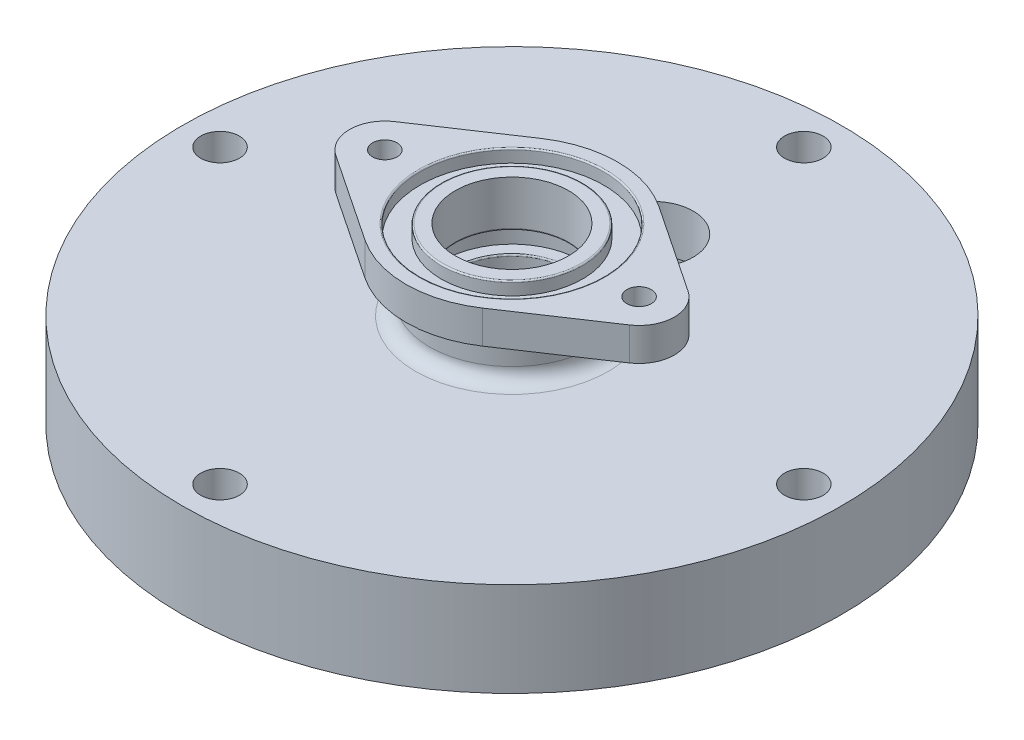
SolidWorks part; units mm, degrees
material "ABS"
ref_plane "Ön Düzlem" through (0, 0, 0) normal (0, 0, 1) x (1, 0, 0)
ref_plane "Üst Düzlem" through (0, 0, 0) normal (0, 1, 0) x (1, 0, 0)
ref_plane "Sağ Düzlem" through (0, 0, 0) normal (1, 0, 0) x (0, 0, -1)
sketch "Çizim1" plane through (0, 0, 0) normal (0, 1, 0) x (1, 0, 0)
  circle A0 centre (0, 0) radius 70
  dimension "D1" = 140
extrude "Yükseklik-Ekstrüzyon1" add sketch "Çizim1" along normal blind 20
sketch "Çizim2" plane through (0, 0, 0) normal (0, -1, 0) x (1, 0, 0)
  circle A0 centre (0, 0) radius 50.03
  circle A1 centre (0, 0) radius 45
  circle A2 centre (0, 0) radius 41
  circle A3 centre (0, 0) radius 17.35
  dimension "D1" = 100.06
  dimension "D2" = 90
  dimension "D3" = 82
  dimension "D4" = 34.7
extrude "Kes-Ekstrüzyon1" cut sketch "Çizim2" against normal blind 10 contours A0 A1 | A2 A3
sketch "Çizim4" plane through (0, 0, 0) normal (0, 0, 1) x (1, 0, 0)
  line L0 (-41, 0) -> (-13.6, 0)
  line L1 (-41, 0) -> (41, 0) construction
  line L2 (-45, 0) -> (45, 0) construction
  line L3 (-17.35, 0) -> (17.35, 0) construction
  line L4 (-17.35, 10) -> (-13.6, 0)
  line L8 (-17.35, 10) -> (17.35, 10) construction
  line L9 (-41, 10) -> (41, 10) construction
  line L10 (-17.35, 0) -> (-17.35, 10)
  line L11 (0, 0) -> (0, 30.5491)
  dimension "D1" = 27.4
revolve "Kes-Döndür1" cut sketch "Çizim4" angle 360 about L11
sketch "Çizim5" plane through (0, 20, 0) normal (0, 1, 0) x (1, 0, 0)
  circle A0 centre (0, 0) radius 17.5
  dimension "D1" = 35
extrude "Yükseklik-Ekstrüzyon2" add sketch "Çizim5" along normal blind 10
sketch "Çizim7" plane through (0, 30, 0) normal (0, 1, 0) x (1, 0, 0)
  line L2 (31.1667, -6.2361) -> (12.5, -18.7083)
  line L3 (31.1667, 6.2361) -> (12.5, 18.7083)
  line L4 (-12.5, -18.7083) -> (-31.1667, -6.2361)
  line L5 (-12.5, 18.7083) -> (-31.1667, 6.2361)
  arc A0 (12.5, 18.7083) -> (-12.5, 18.7083) centre (0, 0) ccw
  circle A1 centre (-27, 0) radius 2.6
  arc A2 (-31.1667, 6.2361) -> (-31.1667, -6.2361) centre (-27, 0) ccw
  circle A3 centre (27, 0) radius 2.6
  arc A4 (31.1667, -6.2361) -> (31.1667, 6.2361) centre (27, 0) ccw
  arc A5 (-12.5, -18.7083) -> (12.5, -18.7083) centre (0, 0) ccw
  dimension "D1" = 45
  dimension "D3" = 5.2
  dimension "D6" = 5.2
  dimension "D2" = 27
  dimension "D5" = 27
extrude "Yükseklik-Ekstrüzyon3" add sketch "Çizim7" along normal blind 7
sketch "Çizim8" plane through (0, 37, 0) normal (0, 1, 0) x (1, 0, 0)
  circle A0 centre (0, 0) radius 12.025
  dimension "D1" = 24.05
extrude "Kes-Ekstrüzyon3" cut sketch "Çizim8" against normal through all
sketch "Çizim9" plane through (0, 37, 0) normal (0, 1, 0) x (1, 0, 0)
  circle A1 centre (0, 0) radius 15.025
  circle A3 centre (0, 0) radius 19.525
  dimension "D1" = 39.05
  dimension "D2" = 30.05
extrude "Kes-Ekstrüzyon4" cut sketch "Çizim9" against normal blind 2.75
fillet "Radyus1" radius 0.3 2 edges at (0, 37, 15.025) (0, 37, 19.525)
fillet "Radyus2" radius 3 2 edges at (0, 30, 17.5) (0, 20, 17.5)
sketch "Çizim10" plane through (0, 0, 0) normal (0, 0, 1) x (1, 0, 0)
  line L0 (-12, 27.2319) -> (-12, 22.7319)
  line L4 (-12, 22.7319) -> (-14.75, 22.7319)
  line L5 (-14.75, 22.7319) -> (-14.75, 27.2319)
  line L6 (-14.75, 27.2319) -> (-12, 27.2319)
  line L7 (0, 0) -> (0, 39.8793)
  dimension "D3" = 12
revolve "Kes-Döndür2" cut sketch "Çizim10" angle 360 about L7
fillet "Radyus3" radius 0.3 2 edges at (0, 27.2319, 12.025) (0, 22.7319, -12.025)
sketch "Çizim11" plane through (0, 0, 0) normal (0, 0, 1) x (1, 0, 0)
  line L0 (-50, 7.375) -> (-50, 2.625)
  line L1 (-50, 2.625) -> (-52.75, 2.625)
  line L2 (-52.75, 2.625) -> (-52.75, 7.375)
  line L6 (-52.75, 7.375) -> (-50, 7.375)
  line L7 (0, 37) -> (0, -25.9971)
  line L8 (12.025, 37) -> (-12.025, 37) construction
  dimension "D1" = 2.75
  dimension "D2" = 4.75
  dimension "D3" = 50
sketch "Çizim12" plane through (0, 20, 0) normal (0, 1, 0) x (1, 0, 0)
  circle A2 centre (0, 62) radius 4.1
  circle A3 centre (62, 0) radius 4.1
  circle A4 centre (0, -62) radius 4.1
  circle A5 centre (-62, 0) radius 4.1
  point P15 (0, 0)
  dimension "D2" = 8.2
  dimension "D3" = 4
extrude "Kes-Ekstrüzyon5" cut sketch "Çizim12" against normal through all
sketch "Çizim13" plane through (0, 20, 0) normal (0, 1, 0) x (1, 0, 0)
  circle A0 centre (0, 30) radius 8.5
  dimension "D1" = 17
  dimension "D2" = 30
extrude "Kes-Ekstrüzyon6" cut sketch "Çizim13" against normal blind 10
sketch "Çizim14" plane through (0, 10, 0) normal (0, -1, 0) x (1, 0, 0)
  circle A0 centre (0, 0) radius 45
  circle A1 centre (0, 0) radius 50.03
extrude "Kes-Ekstrüzyon7" cut sketch "Çizim14" against normal blind 3
